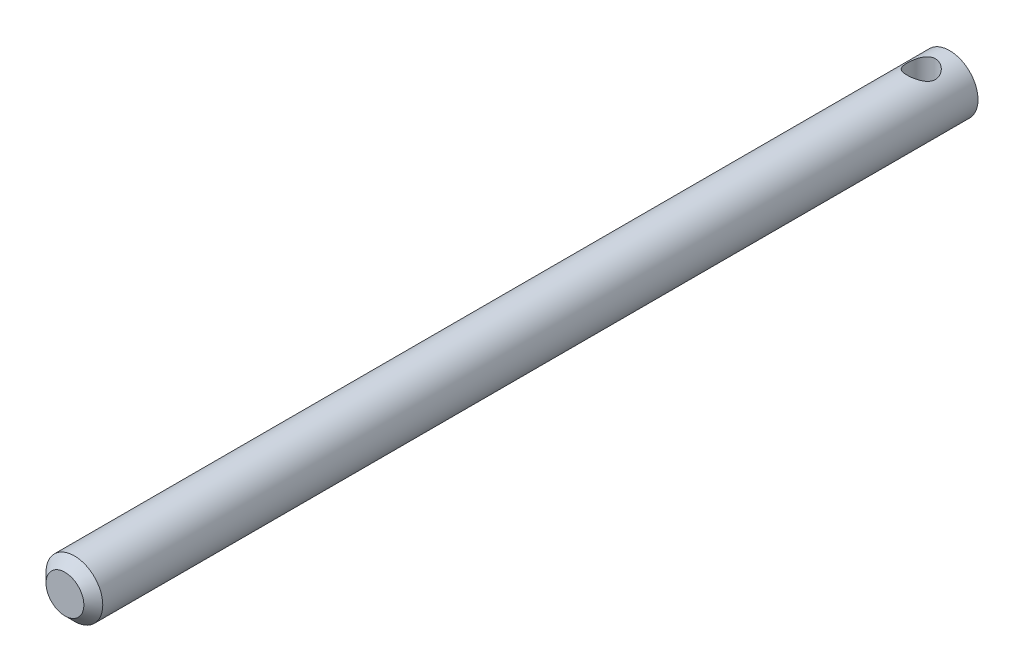
SolidWorks part; units mm, degrees
material "1.5714 (16NiCr4)"
ref_plane "Plan de face" through (0, 0, 0) normal (0, 0, 1) x (1, 0, 0)
ref_plane "Plan de dessus" through (0, 0, 0) normal (0, 1, 0) x (1, 0, 0)
ref_plane "Plan de droite" through (0, 0, 0) normal (1, 0, 0) x (0, 0, -1)
sketch "Esquisse1" plane through (0, 0, 0) normal (0, 0, 1) x (1, 0, 0)
  circle A0 centre (0, 0) radius 3
  dimension "D1" = 6
extrude "Boss.-Extru.1" add sketch "Esquisse1" along normal blind 93.5
sketch "Esquisse2" plane through (0, 0, 0) normal (0, 1, 0) x (1, 0, 0)
  line L0 (3, 0) -> (-3, 0) construction
  circle A0 centre (0, -3) radius 1.5
  dimension "D1" = 3
  dimension "D2" = 3
  dimension "D3" = 0
extrude "Enlèv. mat.-Extru.1" cut sketch "Esquisse2" against normal through all both and the other way through all
chamfer "Chanfrein1" distance 1 angle 45 1 edges at (3, 0, 93.5)
